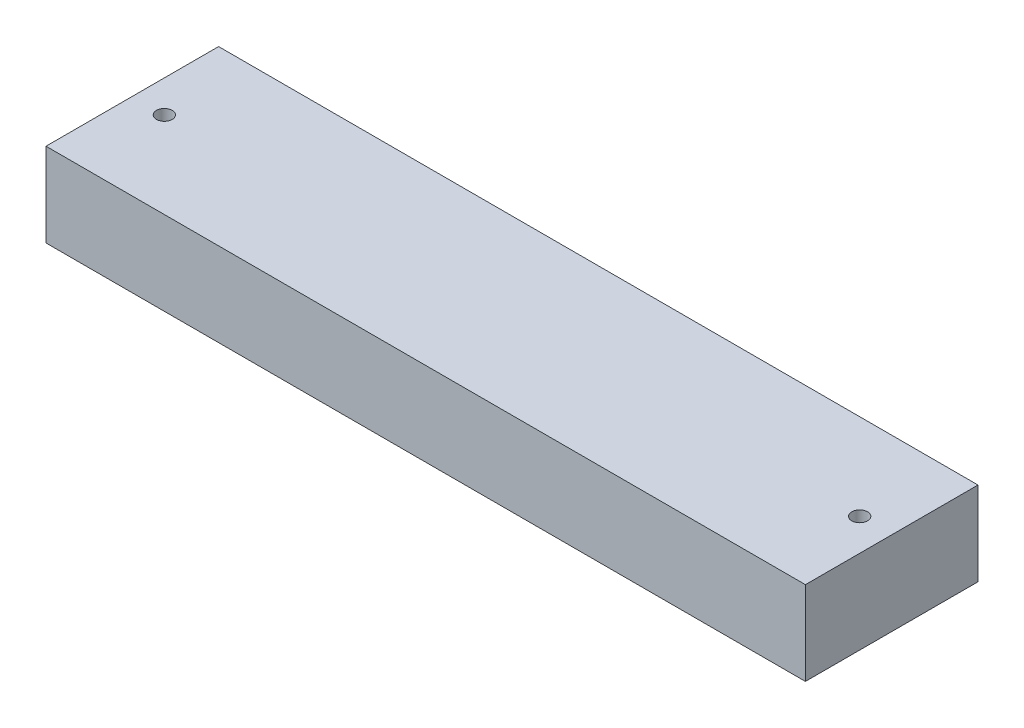
SolidWorks part; units mm, degrees
ref_plane "Front Plane" through (0, 0, 0) normal (0, 0, 1) x (1, 0, 0)
ref_plane "Top Plane" through (0, 0, 0) normal (0, 1, 0) x (1, 0, 0)
ref_plane "Right Plane" through (0, 0, 0) normal (1, 0, 0) x (0, 0, -1)
sketch "Sketch1" plane through (0, 0, 0) normal (0, 1, 0) x (1, 0, 0)
  line L0 (-70.5, 0) -> (70.5, 0) construction
  line L1 (-77, -17.5) -> (77, -17.5)
  line L2 (-77, -17.5) -> (-77, 17.5)
  line L3 (-77, 17.5) -> (77, 17.5)
  line L4 (77, -17.5) -> (77, 17.5)
  line L5 (-77, -17.5) -> (77, 17.5) construction
  line L6 (-77, 17.5) -> (77, -17.5) construction
  point P0 (0, 0)
  point P9 (0, 0)
  dimension "D1" = 154
  dimension "D2" = 141
  dimension "D3" = 35
extrude "Boss-Extrude1" add sketch "Sketch1" along normal blind 17
hole_wizard "M3 Clearance Hole1" positions "Sketch2" profile "Sketch3" hole size "M3" standard "ANSI Metric" end condition through all
sketch "Sketch2" plane through (0, 17, 0) normal (0, 1, 0) x (1, 0, 0)
  point P0 (-70.5, 0)
  point P3 (70.5, 0)
sketch "Sketch3" plane through (-70.5, 17, 0) normal (1, 0, 0) x (0, 0, 1)
  line L0 (0, 0) -> (0, 17)
  line L1 (0, 17) -> (1.6, 17)
  line L2 (1.6, 17) -> (1.6, 0)
  line L5 (1.6, 0) -> (0, 0)
  line L11 (0, -6.35) -> (0, 107.95) construction
  dimension "Thru Hole Dia." = 3.2
  dimension "Thru Hole Depth" = 17
